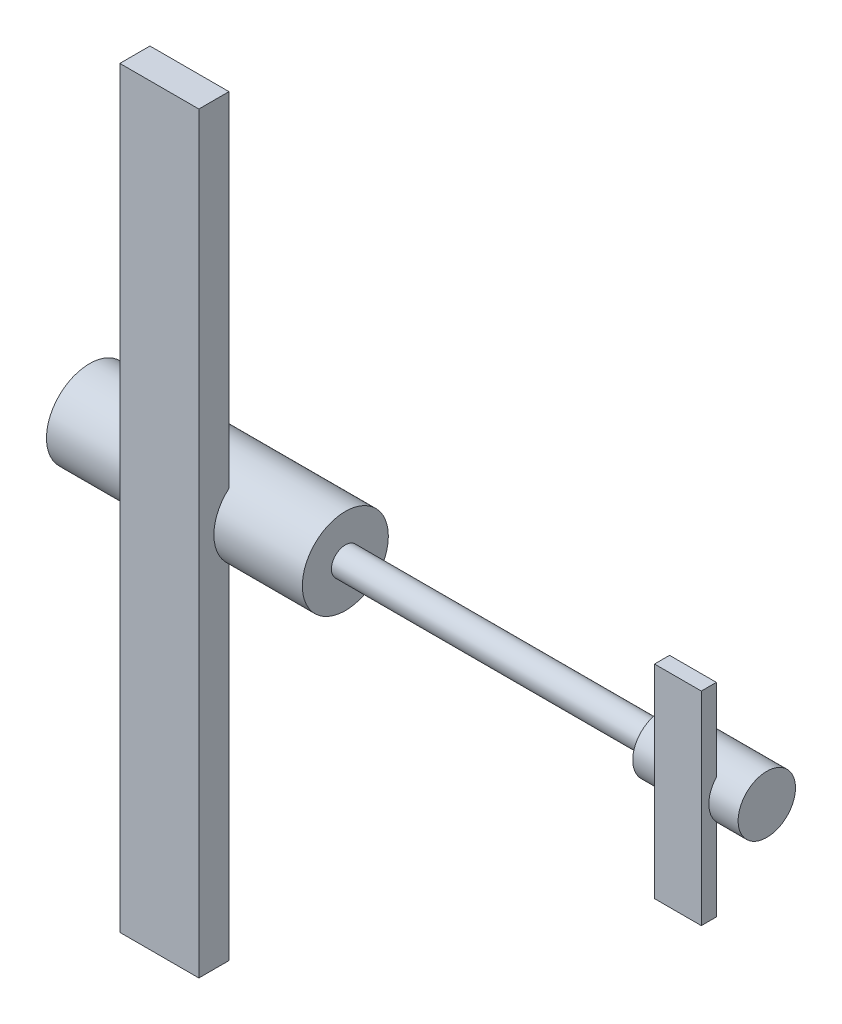
SolidWorks part; units mm, degrees
ref_plane "Front Plane" through (0, 0, 0) normal (1, 0, 0) x (0, 1, 0)
ref_plane "Top Plane" through (0, 0, 0) normal (0, 0, 1) x (0, 1, 0)
ref_plane "Right Plane" through (0, 0, 0) normal (0, 1, 0) x (-1, 0, 0)
sketch "Sketch2" plane through (0, 0, 0) normal (1, 0, 0) x (0, 1, 0)
  circle A0 centre (0, 0) radius 57.15
  dimension "D1" = 114.3
extrude "Boss-Extrude1" add sketch "Sketch2" along normal blind 340
sketch "Sketch3" plane through (340, 0, 0) normal (1, 0, 0) x (0, 1, 0)
  circle A0 centre (0, 0) radius 18.5393
extrude "Boss-Extrude2" add sketch "Sketch3" along normal blind 420
sketch "Sketch4" plane through (760, 0, 0) normal (1, 0, 0) x (0, 1, 0)
  circle A0 centre (0, 0) radius 38.1
  dimension "D1" = 76.2
extrude "Boss-Extrude3" add sketch "Sketch4" along normal blind 140
sketch "Sketch5" plane through (0, 0, 0) normal (0, 1, 0) x (-1, 0, 0)
  line L0 (0, 57.15) -> (-340, 57.15) construction
  line L1 (-222.5, 37.15) -> (-117.5, 37.15)
  line L2 (-222.5, 37.15) -> (-222.5, 77.15)
  line L3 (-222.5, 77.15) -> (-117.5, 77.15)
  line L4 (-117.5, 37.15) -> (-117.5, 77.15)
  line L5 (-222.5, 37.15) -> (-117.5, 77.15) construction
  line L6 (-222.5, 77.15) -> (-117.5, 37.15) construction
  point P0 (-170, 57.15)
  dimension "D1" = 105
  dimension "D2" = 40
extrude "Boss-Extrude4" add sketch "Sketch5" along normal mid plane 1000
sketch "Sketch6" plane through (0, 0, 0) normal (0, 1, 0) x (-1, 0, 0)
  line L0 (-760, 38.1) -> (-900, 38.1) construction
  line L1 (-861.1, 28.1) -> (-798.9, 28.1)
  line L2 (-861.1, 28.1) -> (-861.1, 48.1)
  line L3 (-861.1, 48.1) -> (-798.9, 48.1)
  line L4 (-798.9, 28.1) -> (-798.9, 48.1)
  line L5 (-861.1, 28.1) -> (-798.9, 48.1) construction
  line L6 (-861.1, 48.1) -> (-798.9, 28.1) construction
  point P0 (-830, 38.1)
  dimension "D1" = 62.2
  dimension "D2" = 20
extrude "Boss-Extrude5" add sketch "Sketch6" along normal mid plane 270
